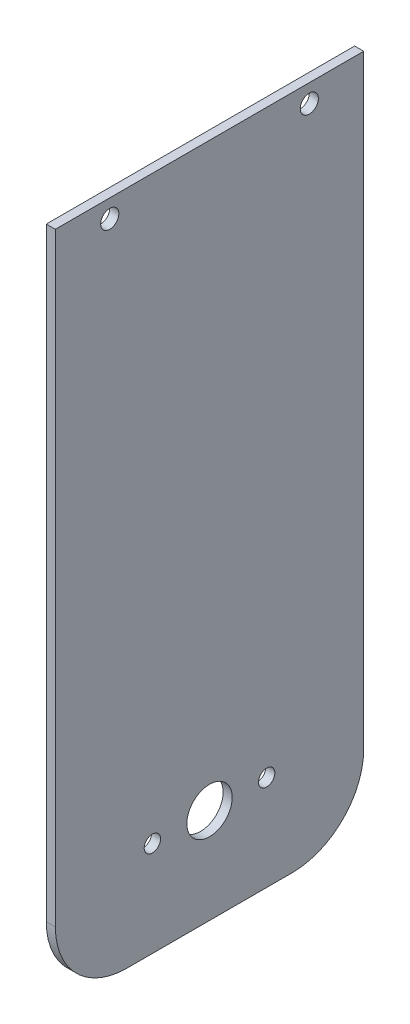
SolidWorks part; units mm, degrees
material "6061-T6 (SS)"
ref_plane "Front Plane" through (0, 0, 0) normal (0, 0, 1) x (1, 0, 0)
ref_plane "Top Plane" through (0, 0, 0) normal (0, 1, 0) x (1, 0, 0)
ref_plane "Right Plane" through (0, 0, 0) normal (1, 0, 0) x (0, 0, -1)
sketch "Sketch1" plane through (0, 0, 0) normal (1, 0, 0) x (0, 0, -1)
  line L0 (-53.975, -84.9275) -> (53.975, -84.9275) construction
  line L1 (-53.975, 118.2675) -> (53.975, 118.2675)
  line L2 (-53.975, 118.2675) -> (-53.975, -118.2675)
  line L3 (-53.975, -118.2675) -> (53.975, -118.2675)
  line L4 (53.975, 118.2675) -> (53.975, -118.2675)
  line L5 (-53.975, 118.2675) -> (53.975, -118.2675) construction
  line L6 (-53.975, -118.2675) -> (53.975, 118.2675) construction
  line L7 (-53.975, 111.9175) -> (53.975, 111.9175) construction
  line L8 (-34.925, 111.9175) -> (-34.925, 115.0925) construction
  line L9 (34.925, 111.9175) -> (34.925, 115.0925) construction
  line L10 (-53.975, 111.9175) -> (-34.925, 111.9175) construction
  line L11 (34.925, 111.9175) -> (53.975, 111.9175) construction
  circle A0 centre (0, -84.9275) radius 7.94
  circle A1 centre (20, -84.9275) radius 2.86
  circle A2 centre (-20, -84.9275) radius 2.86
  circle A3 centre (-34.925, 111.9175) radius 3.175
  circle A4 centre (34.925, 111.9175) radius 3.175
  point P0 (0, 0)
  dimension "D4" = 15.88
  dimension "D6" = 5.72
  dimension "D7" = 5.72
  dimension "D9" = 12.2102
  dimension "D1" = 236.535
  dimension "D2" = 107.95
  dimension "D3" = 33.34
  dimension "D5" = 20
  dimension "D8" = 20
  dimension " 1in/2" = 6.35
  dimension "D10" = 19.05
  dimension "D11" = 19.05
extrude "Boss-Extrude1" add sketch "Sketch1" along normal blind 3.175
fillet "Fillet1" radius 25 2 edges at (1.5875, -118.2675, 53.975) (1.5875, -118.2675, -53.975)
